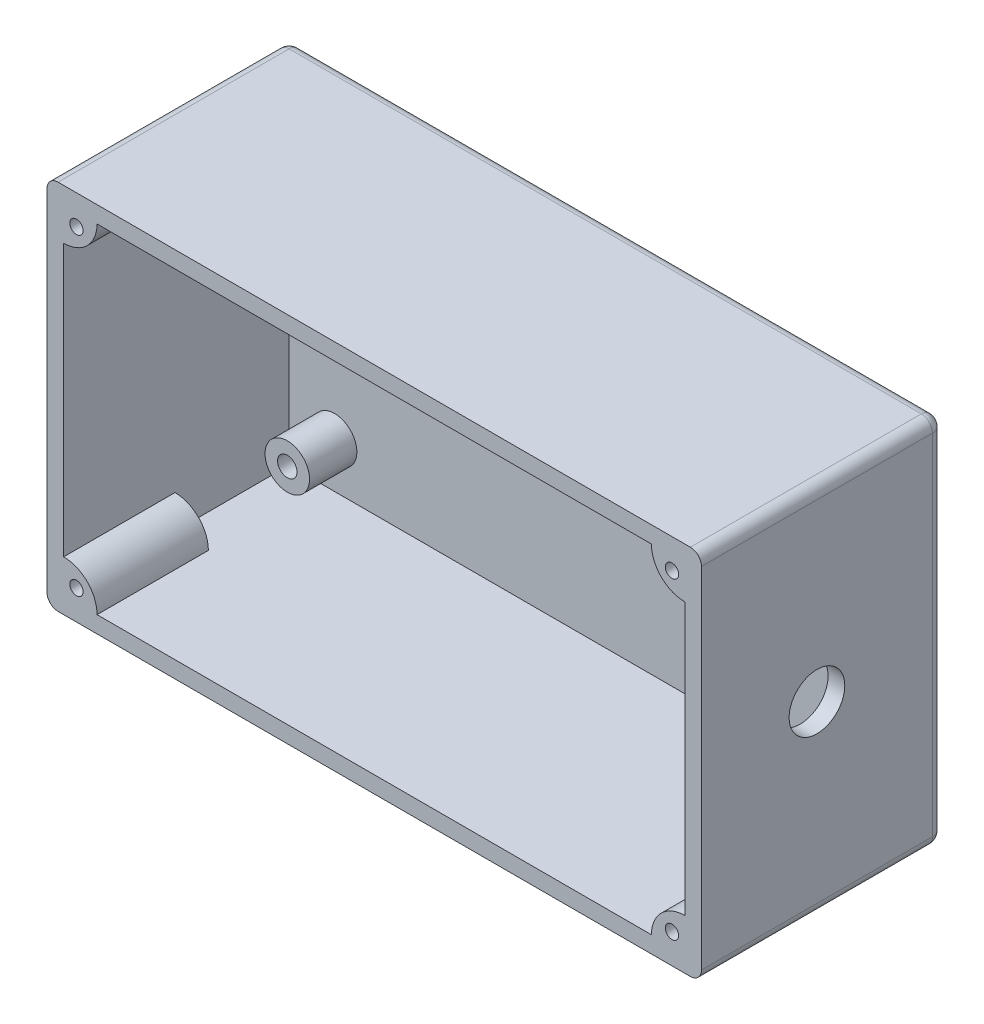
SolidWorks part; units mm, degrees
ref_plane "Piano frontale" through (0, 0, 0) normal (0, 0, 1) x (1, 0, 0)
ref_plane "Piano superiore" through (0, 0, 0) normal (0, 1, 0) x (1, 0, 0)
ref_plane "Piano destro" through (0, 0, 0) normal (1, 0, 0) x (0, 0, -1)
sketch "Schizzo1" plane through (0, 0, 0) normal (0, 0, 1) x (1, 0, 0)
  line L1 (-58.8, -33.4) -> (58.8, -33.4)
  line L2 (-58.8, -33.4) -> (-58.8, 33.4)
  line L3 (-58.8, 33.4) -> (58.8, 33.4)
  line L4 (58.8, -33.4) -> (58.8, 33.4)
  line L5 (-58.8, -33.4) -> (58.8, 33.4) construction
  line L6 (-58.8, 33.4) -> (58.8, -33.4) construction
  point P0 (0, 0)
  dimension "D1" = 117.6
  dimension "D2" = 66.8
extrude "Estrusione-Estrusione1" add sketch "Schizzo1" along normal blind 3
sketch "Schizzo2" plane through (0, 0, 3) normal (0, 0, 1) x (1, 0, 0)
  line L1 (58.8, -33.4) -> (-58.8, -33.4)
  line L2 (58.8, -33.4) -> (58.8, 33.4)
  line L3 (58.8, 33.4) -> (-58.8, 33.4)
  line L4 (-58.8, -33.4) -> (-58.8, 33.4)
  line L5 (58.8, -33.4) -> (-58.8, 33.4) construction
  line L6 (58.8, 33.4) -> (-58.8, -33.4) construction
  line L7 (55.8, -30.4) -> (-55.8, -30.4)
  line L8 (55.8, -30.4) -> (55.8, 30.4)
  line L9 (55.8, 30.4) -> (-55.8, 30.4)
  line L10 (-55.8, -30.4) -> (-55.8, 30.4)
  line L11 (55.8, -30.4) -> (-55.8, 30.4) construction
  line L12 (55.8, 30.4) -> (-55.8, -30.4) construction
  point P0 (0, 0)
  point P7 (0, 0)
  dimension "D1" = 3
  dimension "D2" = 3
extrude "Estrusione- Fori Cover" add sketch "Schizzo2" along normal blind 40.5
sketch "Schizzo4" plane through (0, 0, 3) normal (0, 0, 1) x (1, 0, 0)
  line L0 (-55.8, 30.4) -> (-55.8, -30.4) construction
  line L1 (55.8, 30.4) -> (-55.8, 30.4) construction
  circle A0 centre (-47.62, 22.2) radius 1.75
  circle A1 centre (-47.62, 22.2) radius 4
  circle A2 centre (47.63, 22.2) radius 4
  circle A3 centre (47.63, 22.2) radius 1.75
  circle A4 centre (47.63, -22.25) radius 4
  circle A5 centre (47.63, -22.25) radius 1.75
  circle A6 centre (-47.62, -22.25) radius 4
  circle A7 centre (-47.62, -22.25) radius 1.75
  dimension "D1" = 3.5
  dimension "D4" = 8
  dimension "D2" = 8.18
  dimension "D3" = 8.2
  dimension "D7" = 95.25
  dimension "D8" = 44.45
  dimension "D5" = 2
  dimension "D6" = 2
extrude "Estrusione- Fori PCB" add sketch "Schizzo4" along normal blind 8.5
sketch "Schizzo7" plane through (0, 0, 3) normal (0, 0, 1) x (1, 0, 0)
  line L0 (-55.8, 30.4) -> (-55.8, -30.4) construction
  line L1 (55.8, -30.4) -> (55.8, 30.4) construction
  circle A0 centre (-48.8, 0) radius 3.5
  circle A1 centre (48.8, 0) radius 3.5
  dimension "D1" = 7
  dimension "D2" = 7
  dimension "D3" = 7
extrude "Estrusione-Fori Chassis" add sketch "Schizzo7" along normal blind 1
sketch "Schizzo8" plane through (0, 0, 3) normal (0, 0, 1) x (1, 0, 0)
  circle A0 centre (-48.8, 0) radius 1.85
  circle A1 centre (48.8, 0) radius 1.85
  dimension "D1" = 3.7
extrude "Taglio-Estrusione2" cut sketch "Schizzo8" against normal through all and the other way up to next
fillet "Raccordo3" radius 2 1 edges at (-58.8, 33.4, 21.75)
fillet "Raccordo4" radius 2 1 edges at (58.8, 33.4, 21.75)
fillet "Raccordo5" radius 2 1 edges at (-58.8, -33.4, 21.75)
fillet "Raccordo6" radius 2 1 edges at (58.8, -33.4, 21.75)
fillet "Raccordo7" radius 2 8 edges at (0, -33.4, 0) (-58.2142, -32.8142, 0) (58.8, 0, 0) (58.2142, -32.8142, 0) (-58.8, 0, 0) (-58.2142, 32.8142, 0) (0, 33.4, 0) (58.2142, 32.8142, 0)
sketch "Schizzo9" plane through (0, 0, 43.5) normal (0, 0, 1) x (1, 0, 0)
  line L0 (55.8, 30.4) -> (-55.8, 30.4) construction
  line L1 (-55.8, 30.4) -> (-55.8, -30.4) construction
  line L2 (55.8, -30.4) -> (55.8, 30.4) construction
  line L3 (-55.8, -30.4) -> (55.8, -30.4) construction
  line L4 (-55.8, 24.4) -> (-55.8, 30.4)
  line L5 (-55.8, 30.4) -> (-49.8, 30.4)
  line L6 (49.8, 30.4) -> (55.8, 30.4)
  line L7 (55.8, 30.4) -> (55.8, 24.4)
  line L8 (55.8, -24.4) -> (55.8, -30.4)
  line L9 (55.8, -30.4) -> (49.8, -30.4)
  line L10 (-55.8, -24.4) -> (-55.8, -30.4)
  line L11 (-55.8, -30.4) -> (-49.8, -30.4)
  line L12 (-58.8, 31.4) -> (-58.8, -31.4) construction
  line L13 (-56.8, -33.4) -> (56.8, -33.4) construction
  line L14 (56.8, 33.4) -> (-56.8, 33.4) construction
  line L15 (58.8, -31.4) -> (58.8, 31.4) construction
  arc A0 (-49.8, 30.4) -> (-55.8, 24.4) centre (-55.8, 30.4) cw
  arc A1 (49.8, 30.4) -> (55.8, 24.4) centre (55.8, 30.4) ccw
  arc A2 (55.8, -24.4) -> (49.8, -30.4) centre (55.8, -30.4) ccw
  arc A3 (-55.8, -24.4) -> (-49.8, -30.4) centre (-55.8, -30.4) cw
  circle A4 centre (-53.5, 28.1) radius 1.2
  circle A5 centre (-53.5, -28.1) radius 1.2
  circle A6 centre (53.5, -28.1) radius 1.2
  circle A7 centre (53.5, 28.1) radius 1.2
  dimension "D1" = 6
  dimension "D4" = 2.4
  dimension "D2" = 5.3
  dimension "D3" = 5.3
  dimension "D5" = 5.3
  dimension "D6" = 5.3
extrude "Estrusione-Estrusione6" add sketch "Schizzo9" against normal blind 20
sketch "Schizzo11" plane through (58.8, 0, 0) normal (1, 0, 0) x (0, 0, -1)
  line L0 (-43.5, -31.4) -> (-43.5, 31.4) construction
  line L1 (-43.5, -31.4) -> (-2, -31.4) construction
  line L2 (-2, -33.4) -> (-43.5, -33.4) construction
  circle A0 centre (-22.75, 0) radius 5
  point P5 (-43.5, 0)
  point P9 (-22.75, -31.4)
  dimension "D1" = 10
  dimension "D2" = 20.75
  dimension "D3" = 33.4
extrude "Taglio- Foro Cavi" cut sketch "Schizzo11" against normal up to next
